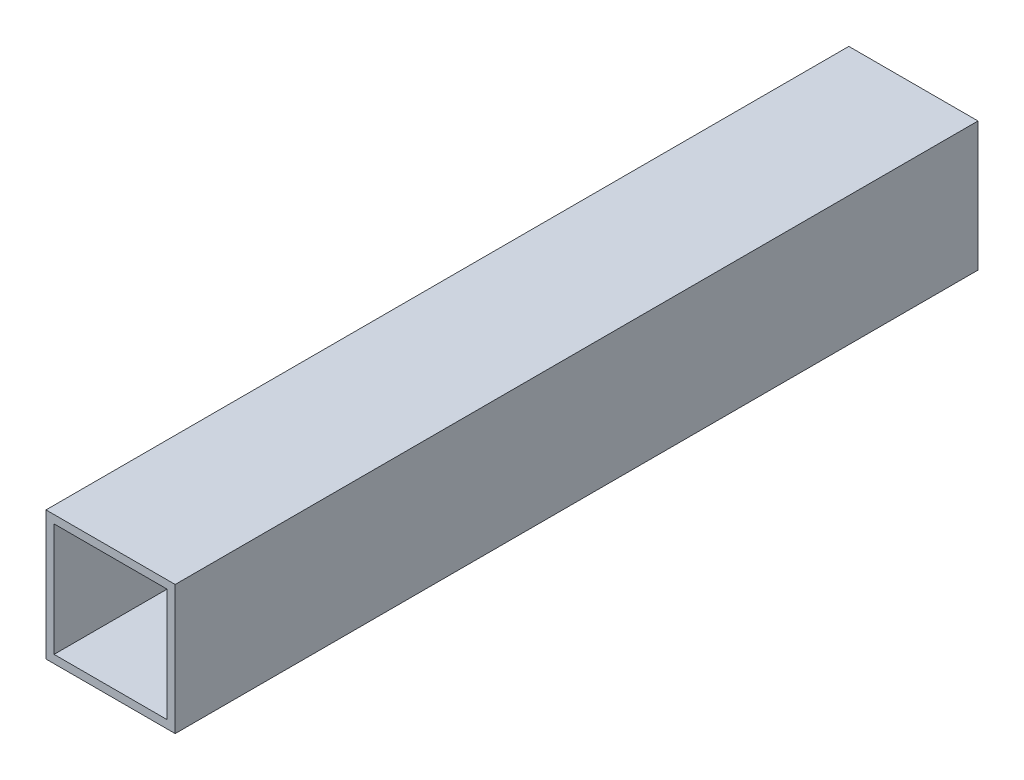
SolidWorks part; units mm, degrees
ref_plane "Front Plane" through (0, 0, 0) normal (0, 0, 1) x (1, 0, 0)
ref_plane "Top Plane" through (0, 0, 0) normal (0, 1, 0) x (1, 0, 0)
ref_plane "Right Plane" through (0, 0, 0) normal (1, 0, 0) x (0, 0, -1)
sketch "Sketch1" plane through (0, 0, 0) normal (0, 0, 1) x (1, 0, 0)
  line L1 (-8.7144, 37.8298) -> (42.0856, 37.8298)
  line L2 (-8.7144, 37.8298) -> (-8.7144, -12.9702)
  line L3 (-8.7144, -12.9702) -> (42.0856, -12.9702)
  line L4 (42.0856, 37.8298) -> (42.0856, -12.9702)
  line L5 (-5.5394, 34.6548) -> (38.9106, 34.6548)
  line L6 (-5.5394, 34.6548) -> (-5.5394, -9.7952)
  line L7 (-5.5394, -9.7952) -> (38.9106, -9.7952)
  line L8 (38.9106, 34.6548) -> (38.9106, -9.7952)
  dimension "D1" = 3.175
  dimension "D2" = 3.175
  dimension "D3" = 3.175
  dimension "D4" = 3.175
  dimension "D5" = 50.8
extrude "Boss-Extrude1" add sketch "Sketch1" along normal blind 315.722
equation "\"D2@Sketch1\"= \"D1@Sketch1\""
equation "\"D3@Sketch1\"= \"D1@Sketch1\""
equation "\"D4@Sketch1\"= \"D1@Sketch1\""
